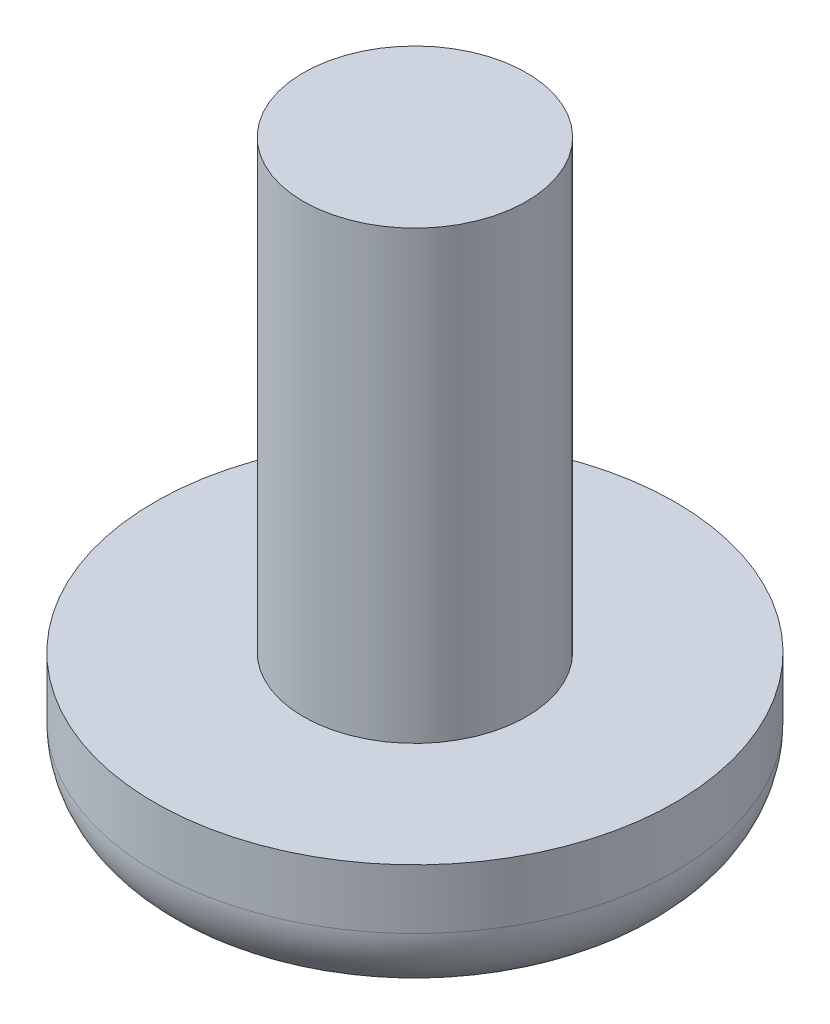
SolidWorks part; units mm, degrees
material "AISI 304"
ref_plane "前视基准面" through (0, 0, 0) normal (0, 0, 1) x (1, 0, 0)
ref_plane "上视基准面" through (0, 0, 0) normal (0, 1, 0) x (1, 0, 0)
ref_plane "右视基准面" through (0, 0, 0) normal (1, 0, 0) x (0, 0, -1)
other "Configuration Table"
sketch "草图1" plane through (0, 0, 0) normal (0, 1, 0) x (1, 0, 0)
  circle A0 centre (0, 0) radius 1.5
  point P2 (0, 0)
  dimension "D1" = 3
extrude "凸台-拉伸1" add sketch "草图1" along normal blind 6
sketch "草图2" plane through (0, 0, 0) normal (0, -1, 0) x (1, 0, 0)
  circle A0 centre (0, 0) radius 3.5
  point P2 (0, 0)
  dimension "D1" = 7
extrude "凸台-拉伸2" add sketch "草图2" along normal blind 1.8
sketch "草图3" plane through (0, -1.8, 0) normal (0, -1, 0) x (1, 0, 0)
  line L0 (0, 0) -> (0, 3.1316) construction
  line L1 (1, 0.5774) -> (0, 1.1547)
  line L2 (0, 1.1547) -> (-1, 0.5774)
  line L3 (-1, 0.5774) -> (-1, -0.5774)
  line L4 (-1, -0.5774) -> (0, -1.1547)
  line L5 (0, -1.1547) -> (1, -0.5774)
  line L6 (1, -0.5774) -> (1, 0.5774)
  circle A0 centre (0, 0) radius 1 construction
  point P1 (0, 1.1547)
  dimension "D1" = 2
extrude "切除-拉伸1" cut sketch "草图3" against normal blind 1
fillet "圆角1" radius 1 1 edges at (0, -1.8, -3.5)
